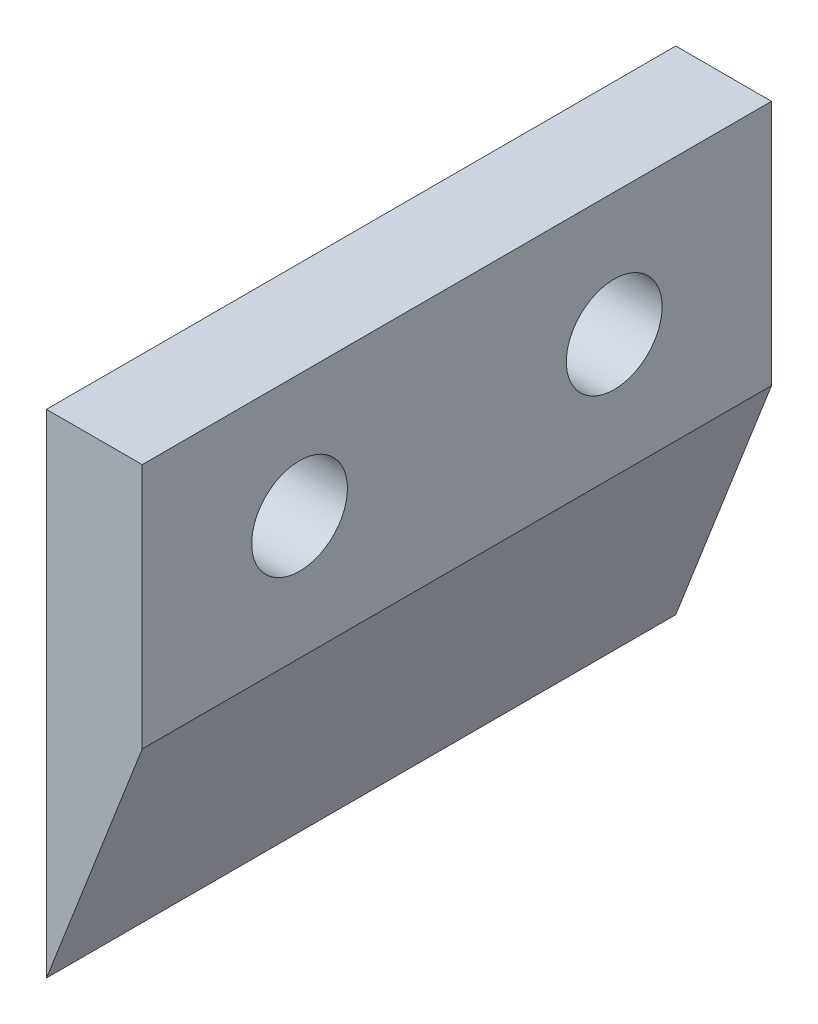
SolidWorks part; units mm, degrees
material "AISI 316 Stainless Steel Sheet (SS)"
ref_plane "Front Plane" through (0, 0, 0) normal (0, 0, 1) x (1, 0, 0)
ref_plane "Top Plane" through (0, 0, 0) normal (0, 1, 0) x (1, 0, 0)
ref_plane "Right Plane" through (0, 0, 0) normal (1, 0, 0) x (0, 0, -1)
sketch "Sketch1" plane through (0, 0, 0) normal (1, 0, 0) x (0, 0, -1)
  line L1 (0, 0) -> (23, 0)
  line L2 (0, 0) -> (0, 18)
  line L3 (0, 18) -> (23, 18)
  line L4 (23, 0) -> (23, 18)
  dimension "D1" = 18
  dimension "D2" = 23
extrude "Boss-Extrude1" add sketch "Sketch1" along normal blind 3.5
sketch "Sketch2" plane through (0, 0, 0) normal (0, 0, 1) x (1, 0, 0)
  line L0 (3.5, 9) -> (0, 0)
  line L1 (3.5, 18) -> (3.5, 0) construction
  line L2 (3.5, 0) -> (3.5, 9)
  line L3 (3.5, 0) -> (0, 0)
extrude "Cut-Extrude1" cut sketch "Sketch2" against normal through all
sketch "Sketch3" plane through (3.5, 0, 0) normal (1, 0, 0) x (0, 0, -1)
  circle A0 centre (5.75, 13.5) radius 1.75
  circle A1 centre (17.25, 13.5) radius 1.75
  dimension "D1" = 3.5
  dimension "D2" = 3.5
extrude "Cut-Extrude3" cut sketch "Sketch3" against normal through all
